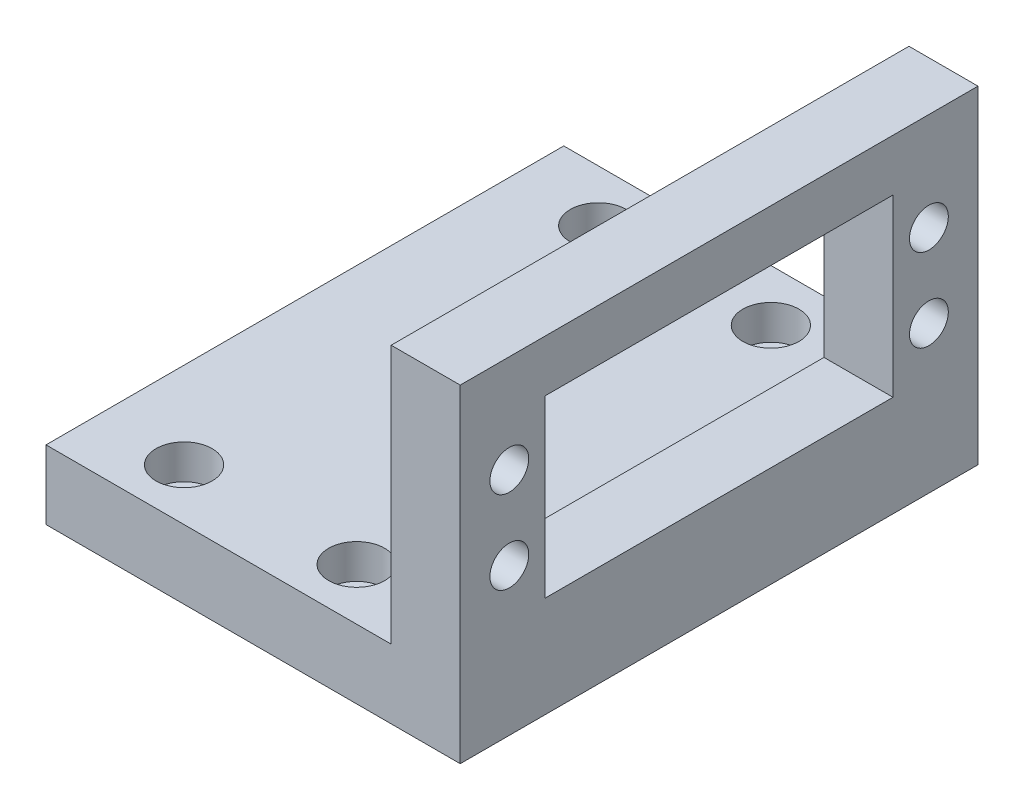
SolidWorks part; units mm, degrees
ref_plane "Alzado" through (0, 0, 0) normal (0, 0, 1) x (1, 0, 0)
ref_plane "Planta" through (0, 0, 0) normal (0, 1, 0) x (1, 0, 0)
ref_plane "Vista lateral" through (0, 0, 0) normal (1, 0, 0) x (0, 0, -1)
sketch "Croquis1" plane through (0, 0, 0) normal (0, 0, 1) x (1, 0, 0)
  line L1 (0, 0) -> (-40, 0)
  line L2 (0, 0) -> (0, -8)
  line L3 (0, -8) -> (-40, -8)
  line L4 (-40, 0) -> (-40, -8)
  line L5 (0, -8) -> (8, -8)
  line L6 (0, -8) -> (0, 30)
  line L7 (0, 30) -> (8, 30)
  line L8 (8, -8) -> (8, 30)
  dimension "D1" = 8
  dimension "D2" = 40
  dimension "D3" = 38
  dimension "D4" = 8
extrude "Saliente-Extruir1" add sketch "Croquis1" along normal mid plane 60 contours L1 L4 L3 L2 | L5 L8 L7 L6 L2
sketch "Croquis2" plane through (8, 0, 0) normal (1, 0, 0) x (0, 0, -1)
  line L0 (-30, 30) -> (30, 30) construction
  line L1 (-20.15, 24) -> (20.15, 24)
  line L2 (-20.15, 24) -> (-20.15, 3.7)
  line L3 (-20.15, 3.7) -> (20.15, 3.7)
  line L4 (20.15, 24) -> (20.15, 3.7)
  line L5 (0, 33.3379) -> (0, -15.0365) construction
  dimension "D1" = 6
  dimension "D2" = 20.3
  dimension "D3" = 40.3
extrude "Cortar-Extruir1" cut sketch "Croquis2" against normal blind 60
sketch "Croquis3" plane through (8, 0, 0) normal (1, 0, 0) x (0, 0, -1)
  line L0 (20.15, 24) -> (-20.15, 24) construction
  line L1 (20.15, 24) -> (-20.15, 24)
  line L2 (20.15, 3.7) -> (20.15, 24) construction
  line L3 (-20.15, 3.7) -> (20.15, 3.7) construction
  line L4 (-20.15, 24) -> (-20.15, 3.7) construction
  line L5 (20.15, 3.7) -> (20.15, 24)
  line L6 (-20.15, 3.7) -> (20.15, 3.7)
  line L7 (-20.15, 24) -> (-20.15, 3.7)
  line L8 (-34.742, 13.85) -> (34.5725, 13.85) construction
  line L9 (0, -9.8354) -> (0, 34.6453) construction
  circle A0 centre (-24.31, 18.65) radius 2.25
  circle A1 centre (-24.31, 9.05) radius 2.25
  circle A2 centre (24.31, 9.05) radius 2.25
  circle A3 centre (24.31, 18.65) radius 2.25
  point P6 (-20.15, 13.85)
  dimension "D2" = 4.5
  dimension "D1" = 4.16
  dimension "D3" = 4.8
extrude "Cortar-Extruir2" cut sketch "Croquis3" against normal blind 60
sketch "Croquis4" plane through (0, 0, 0) normal (0, 1, 0) x (1, 0, 0)
  line L0 (21.0322, 0) -> (-56.1812, 0) construction
  line L1 (-40, -30) -> (-40, 30) construction
  line L2 (-20, 30) -> (-20, -30) construction
  line L3 (0, 30) -> (-40, 30) construction
  line L4 (0, -30) -> (-40, -30) construction
  circle A0 centre (-30, 24) radius 3.25
  circle A1 centre (-10, 24) radius 3.25
  circle A2 centre (-10, -24) radius 3.25
  circle A3 centre (-30, -24) radius 3.25
  dimension "D2" = 6.5
  dimension "D1" = 10
  dimension "D3" = 24
extrude "Cortar-Extruir3" cut sketch "Croquis4" against normal blind 4
hole_wizard "Taladro de margen para M31" positions "Croquis3D1" profile "Croquis7" hole size "M3" standard "DIN"
sketch3d "Croquis3D1"
  line L0 (-30, -4, -24) -> (-30, 0, -24) construction
  line L1 (-10, -4, -24) -> (-10, 0, -24) construction
  line L2 (-10, -4, 24) -> (-10, 0, 24) construction
  line L3 (-30, -4, 24) -> (-30, 0, 24) construction
  point P0 (-30, -4, -24)
  point P4 (-10, -4, -24)
  point P8 (-10, 0, 24)
  point P12 (-30, -4, 24)
sketch "Croquis7" plane through (-30, -4, -24) normal (1, 0, 0) x (0, 0, 1)
  line L0 (0, 0) -> (0, 12.5215)
  line L1 (0, 12.5215) -> (1.7, 11.5)
  line L2 (1.7, 11.5) -> (1.7, 0)
  line L5 (1.7, 0) -> (0, 0)
  line L10 (0, 12.5215) -> (-1.7, 11.5) construction
  line L11 (0, -6.35) -> (0, 107.95) construction
  dimension "Diámetro de taladro" = 3.4
  dimension "Profundidad de taladro" = 11.5
  dimension "Ángulo de perforador" = 118
